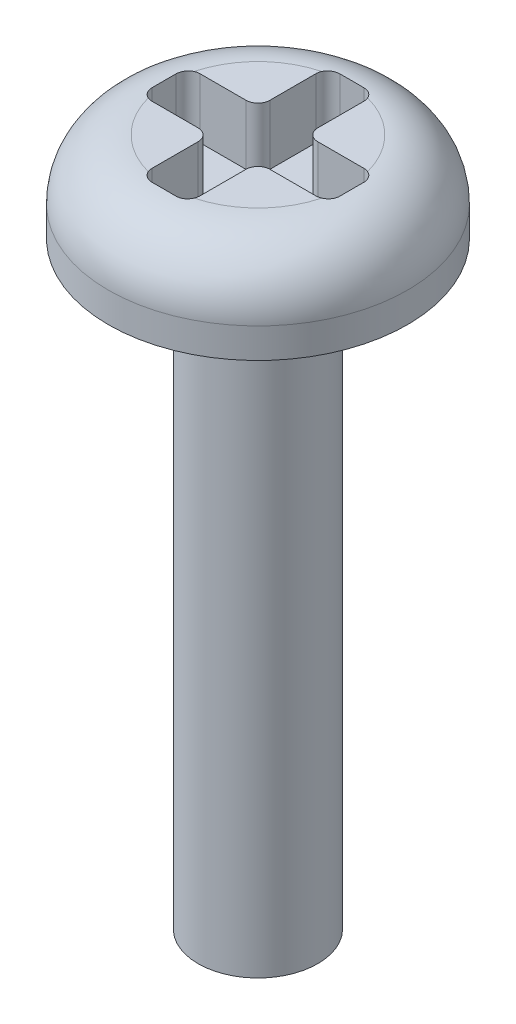
SolidWorks part; units mm, degrees
ref_plane "Front Plane" through (0, 0, 0) normal (0, 0, 1) x (1, 0, 0)
ref_plane "Top Plane" through (0, 0, 0) normal (0, 1, 0) x (1, 0, 0)
ref_plane "Right Plane" through (0, 0, 0) normal (1, 0, 0) x (0, 0, -1)
sketch "Sketch1" plane through (0, 0, 0) normal (0, 1, 0) x (1, 0, 0)
  circle A0 centre (0, 0) radius 1
  dimension "D1" = 2
extrude "Boss-Extrude1" add sketch "Sketch1" along normal blind 10
sketch "Sketch2" plane through (0, 10, 0) normal (0, 1, 0) x (1, 0, 0)
  circle A0 centre (0, 0) radius 2.5
  dimension "D1" = 5
extrude "Boss-Extrude2" add sketch "Sketch2" along normal blind 1.5
fillet "Fillet1" radius 1 1 edges at (0, 11.5, 2.5)
sketch "Sketch3" plane through (0, 11.5, 0) normal (0, 1, 0) x (1, 0, 0)
  line L0 (-0.4, 0.6) -> (-0.4, 1.3699)
  line L1 (1.37, -0.4) -> (0.6, -0.4)
  line L2 (1.57, -0.2) -> (1.57, 0.2)
  line L3 (1.37, 0.4) -> (0.6, 0.4)
  line L4 (-1.57, -0.2) -> (-1.57, 0.2)
  line L5 (1.57, -0.4) -> (-1.57, 0.4) construction
  line L6 (1.57, 0.4) -> (-1.57, -0.4) construction
  line L7 (0.2, -1.5699) -> (-0.2, -1.5699)
  line L8 (0.4, -1.3699) -> (0.4, -0.6)
  line L9 (0.2, 1.5699) -> (-0.2, 1.5699)
  line L10 (-0.4, -1.3699) -> (-0.4, -0.6)
  line L11 (0.4, -1.5699) -> (-0.4, 1.5699) construction
  line L12 (0.4, 1.5699) -> (-0.4, -1.5699) construction
  line L13 (0.4, 0.6) -> (0.4, 1.3699)
  line L14 (-0.6, -0.4) -> (-1.37, -0.4)
  line L15 (-0.6, 0.4) -> (-1.37, 0.4)
  arc A0 (-0.4, -0.6) -> (-0.6, -0.4) centre (-0.6, -0.6) ccw
  arc A1 (-1.57, -0.2) -> (-1.37, -0.4) centre (-1.37, -0.2) ccw
  arc A2 (-1.37, 0.4) -> (-1.57, 0.2) centre (-1.37, 0.2) ccw
  arc A3 (-0.4, 0.6) -> (-0.6, 0.4) centre (-0.6, 0.6) cw
  arc A4 (-0.2, 1.5699) -> (-0.4, 1.3699) centre (-0.2, 1.3699) ccw
  arc A5 (0.4, 1.3699) -> (0.2, 1.5699) centre (0.2, 1.3699) ccw
  arc A6 (0.6, 0.4) -> (0.4, 0.6) centre (0.6, 0.6) cw
  arc A7 (1.57, 0.2) -> (1.37, 0.4) centre (1.37, 0.2) ccw
  arc A8 (1.57, -0.2) -> (1.37, -0.4) centre (1.37, -0.2) cw
  arc A9 (0.6, -0.4) -> (0.4, -0.6) centre (0.6, -0.6) ccw
  arc A10 (0.4, -1.3699) -> (0.2, -1.5699) centre (0.2, -1.3699) cw
  arc A11 (-0.4, -1.3699) -> (-0.2, -1.5699) centre (-0.2, -1.3699) ccw
  point P0 (0, 0)
  point P6 (0, 0)
  point P17 (-0.4, -0.4)
  point P26 (-0.4, 0.4)
  dimension "D5" = 0.2
  dimension "D1" = 0.8
  dimension "D2" = 3.14
  dimension "D3" = 0.8
  dimension "D4" = 3.1398
extrude "Cut-Extrude1" cut sketch "Sketch3" against normal blind 1
